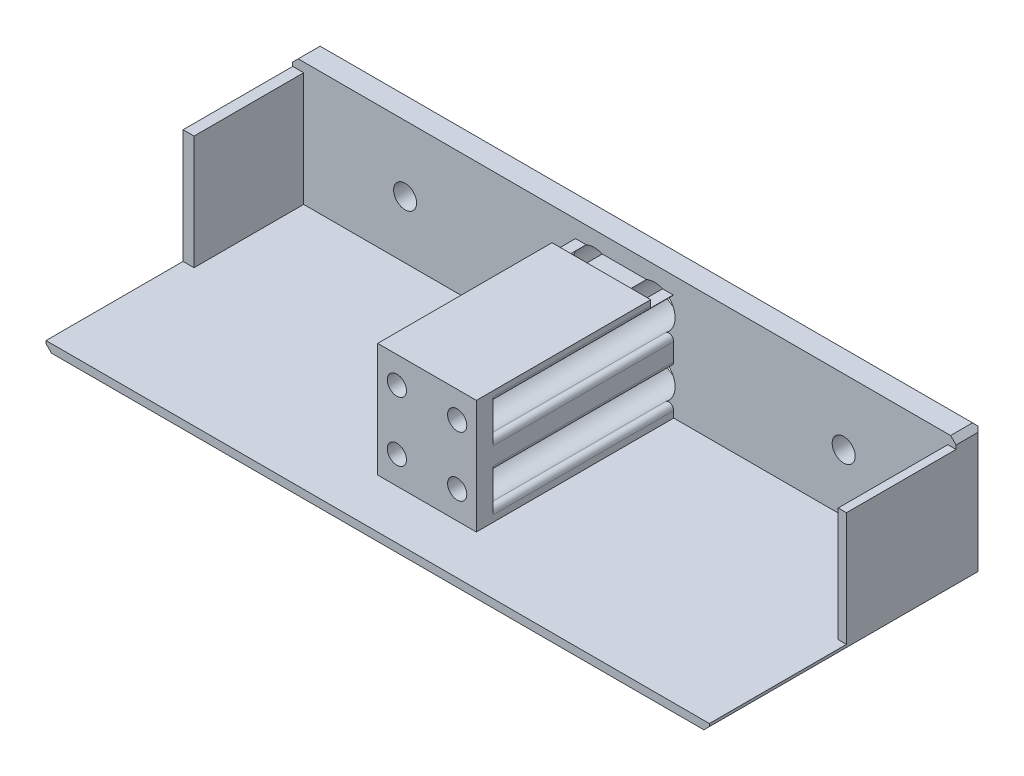
SolidWorks part; units mm, degrees
material "ABS"
ref_plane "Płaszczyzna przednia" through (0, 0, 0) normal (0, 0, 1) x (1, 0, 0)
ref_plane "Płaszczyzna górna" through (0, 0, 0) normal (0, 1, 0) x (1, 0, 0)
ref_plane "Płaszczyzna prawa" through (0, 0, 0) normal (1, 0, 0) x (0, 0, -1)
sketch "Szkic1" plane through (0, 0, 0) normal (0, 0, 1) x (1, 0, 0)
  line L0 (-40, 0) -> (40, 0) construction
  line L1 (-60.5, 12) -> (60.5, 12)
  line L2 (-60.5, 12) -> (-60.5, -12)
  line L3 (-60.5, -12) -> (60.5, -12)
  line L4 (60.5, 12) -> (60.5, -12)
  line L5 (-60.5, 12) -> (60.5, -12) construction
  line L6 (-60.5, -12) -> (60.5, 12) construction
  line L7 (0, 12) -> (0, -12) construction
  circle A0 centre (-40, 0) radius 2.1
  circle A1 centre (40, 0) radius 2.1
  point P0 (0, 0)
  dimension "D1" = 4.2
  dimension "D2" = 80
  dimension "D3" = 20.5
  dimension "D4" = 24
extrude "Dodanie-wyciągnięcie1" add sketch "Szkic1" along normal blind 5
sketch "Szkic2" plane through (0, 0, 5) normal (0, 0, 1) x (1, 0, 0)
  line L1 (-9, -10.5) -> (9, -10.5)
  line L2 (-9, -10.5) -> (-9, 10.5)
  line L3 (-9, 10.5) -> (9, 10.5)
  line L4 (9, -10.5) -> (9, 10.5)
  line L5 (-9, -10.5) -> (9, 10.5) construction
  line L6 (-9, 10.5) -> (9, -10.5) construction
  circle A0 centre (-40, 0) radius 2.1 construction
  point P0 (0, 0)
  dimension "D1" = 21
  dimension "D2" = 31
  dimension "D3" = 18
extrude "Dodanie-wyciągnięcie2" add sketch "Szkic2" along normal blind 36
sketch "Szkic3" plane through (0, 0, 41) normal (0, 0, 1) x (1, 0, 0)
  line L0 (-9, 10.5) -> (-9, -10.5) construction
  line L1 (22.55, 0) -> (-22.55, 0) construction
  line L2 (0, -13.2) -> (0, 13.2) construction
  circle A0 centre (-5.5, 5.45) radius 1.75
  circle A1 centre (-5.5, -5.45) radius 1.75
  circle A2 centre (5.5, -5.45) radius 1.75
  circle A3 centre (5.5, 5.45) radius 1.75
  dimension "D1" = 3.5
  dimension "D2" = 3.5
  dimension "D3" = 5.45
extrude "Wytnij-wyciągnięcie1" cut sketch "Szkic3" against normal up to next
sketch "Szkic4" plane through (0, 0, 0) normal (0, 0, -1) x (-1, 0, 0)
  circle A0 centre (-5.5, 5.45) radius 3.75
  circle A1 centre (-5.5, -5.45) radius 3.75
  circle A2 centre (5.5, 5.45) radius 3.75
  circle A3 centre (5.5, -5.45) radius 3.75
  dimension "D1" = 7.5
extrude "Wytnij-wyciągnięcie2" cut sketch "Szkic4" against normal offset from surface (38 mm away) 3 up to face at (3.75, 5.45, 41)
fillet "Zaokrąglenie1" radius 0.9 8 edges at (9, -4.1037, 21.5) (9, -6.7963, 21.5) (9, 4.1037, 21.5) (9, 6.7963, 21.5) (-9, -4.1037, 21.5) (-9, -6.7963, 21.5) (-9, 4.1037, 21.5) (-9, 6.7963, 21.5)
sketch "Szkic5" plane through (0, 0, 5) normal (0, 0, 1) x (1, 0, 0)
  line L0 (-60.5, -12) -> (-60.5, -10.5)
  line L1 (-60.5, -12) -> (60.5, -12)
  line L2 (-60.5, -10.5) -> (60.5, -10.5)
  line L3 (60.5, -12) -> (60.5, -10.5)
  line L4 (-60.5, 12) -> (-60.5, -12) construction
  line L7 (60.5, -12) -> (60.5, 12) construction
  dimension "D1" = 1.5
extrude "Dodanie-wyciągnięcie3" add sketch "Szkic5" along normal blind 45 contours L1 L3 L2 L0
sketch "Szkic6" plane through (0, 10.5, 0) normal (0, 1, 0) x (1, 0, 0)
  line L1 (-9, -41) -> (9, -41)
  line L2 (-9, -41) -> (-9, -5)
  line L3 (-9, -5) -> (9, -5)
  line L4 (9, -41) -> (9, -5)
extrude "Wytnij-wyciągnięcie3" cut sketch "Szkic6" against normal blind 0.2
sketch "Szkic7" plane through (0, 10.3, 0) normal (0, 1, 0) x (1, 0, 0)
  line L0 (9, -41) -> (9, -5) construction
  line L1 (-9, -5) -> (9, -5)
  line L2 (-9, -5) -> (-9, -9.2)
  line L3 (-9, -9.2) -> (9, -9.2)
  line L4 (9, -5) -> (9, -9.2)
  dimension "D1" = 4.2
extrude "Wytnij-wyciągnięcie4" cut sketch "Szkic7" against normal blind 1.4
sketch "Szkic8" plane through (0, -10.5, 0) normal (0, 1, 0) x (1, 0, 0)
  line L1 (-60.5, -5) -> (-58.5, -5)
  line L2 (-60.5, -5) -> (-60.5, -25)
  line L3 (-60.5, -25) -> (-58.5, -25)
  line L4 (-58.5, -5) -> (-58.5, -25)
  line L5 (60.5, -5) -> (59, -5)
  line L6 (60.5, -5) -> (60.5, -25)
  line L7 (60.5, -25) -> (59, -25)
  line L8 (59, -5) -> (59, -25)
  dimension "D1" = 20
  dimension "D2" = 2
  dimension "D3" = 20
  dimension "D4" = 1.5
extrude "Dodanie-wyciągnięcie4" add sketch "Szkic8" along normal up to surface (20.8 mm away) up to face at (0, 10.3, 25.1)
chamfer "Sfazowanie1" distance 1 angle 45 4 edges at (0, 12, 0) (-60.5, 0, 0) (0, -12, 0) (60.5, 0, 0)
chamfer "Sfazowanie2" distance 1 angle 45 4 edges at (60.5, -12, 25.5) (60.5, 12, 3) (-60.5, -12, 25.5) (-60.5, 12, 3)
